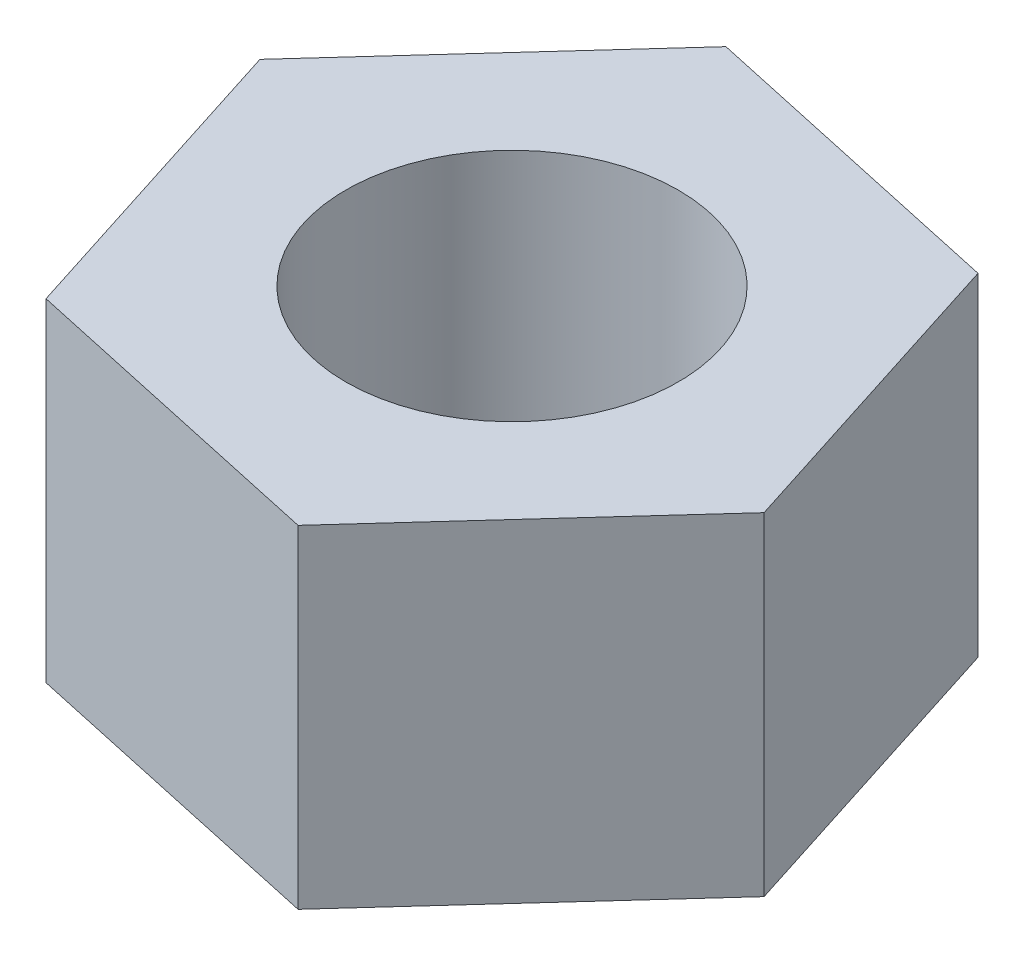
SolidWorks part; units mm, degrees
ref_plane "Front Plane" through (0, 0, 0) normal (0, 0, 1) x (1, 0, 0)
ref_plane "Top Plane" through (0, 0, 0) normal (0, 1, 0) x (1, 0, 0)
ref_plane "Right Plane" through (0, 0, 0) normal (1, 0, 0) x (0, 0, -1)
sketch "Sketch1" plane through (0, 0, 0) normal (0, 1, 0) x (1, 0, 0)
  line L1 (0.905, -2.835) -> (2.9077, -0.6337)
  line L2 (2.9077, -0.6337) -> (2.0027, 2.2013)
  line L3 (2.0027, 2.2013) -> (-0.905, 2.835)
  line L4 (-0.905, 2.835) -> (-2.9077, 0.6337)
  line L5 (-2.9077, 0.6337) -> (-2.0027, -2.2013)
  line L6 (-2.0027, -2.2013) -> (0.905, -2.835)
  circle A0 centre (0, 0) radius 1.5
  circle A1 centre (0, 0) radius 2.5772 construction
extrude "Boss-Extrude1" add sketch "Sketch1" along normal blind 3
